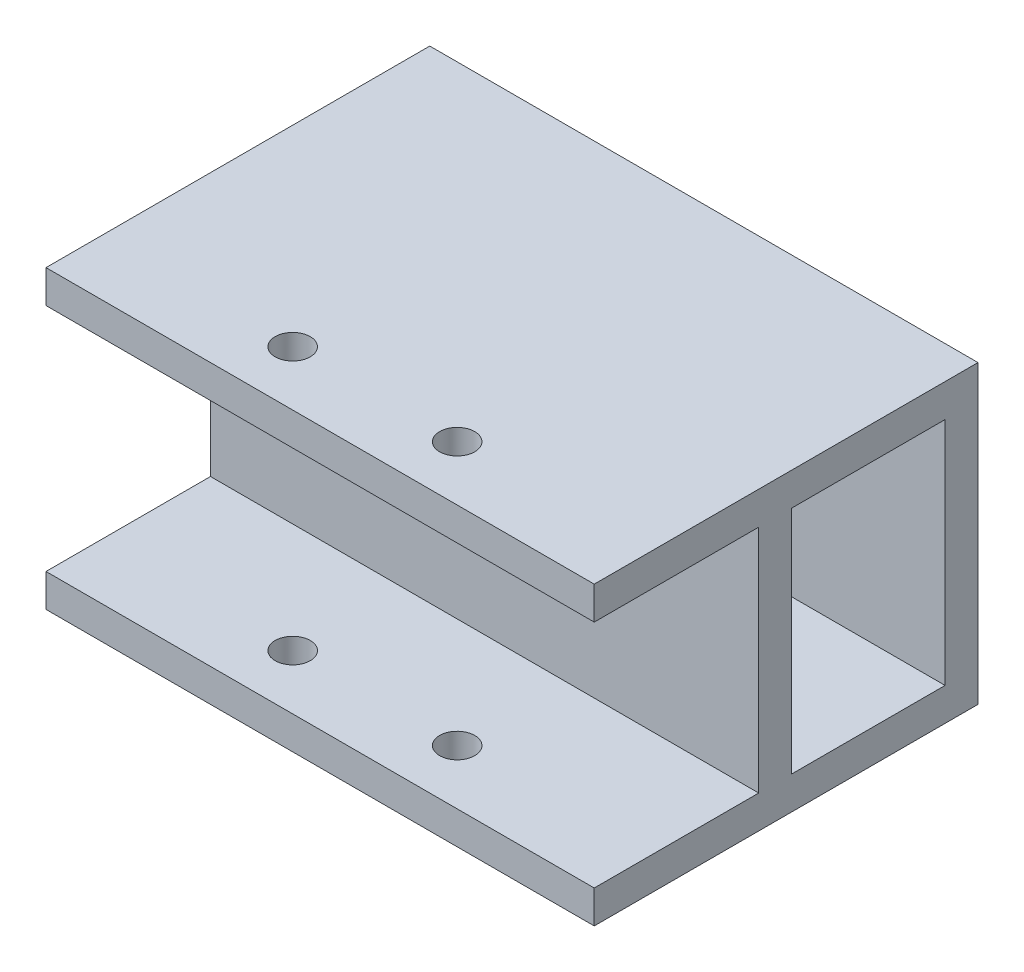
SolidWorks part; units mm, degrees
ref_plane "前视基准面" through (0, 0, 0) normal (0, 0, 1) x (1, 0, 0)
ref_plane "上视基准面" through (0, 0, 0) normal (0, 1, 0) x (1, 0, 0)
ref_plane "右视基准面" through (0, 0, 0) normal (1, 0, 0) x (0, 0, -1)
other "Configuration Table"
sketch "草图1" plane through (0, 0, 0) normal (0, 0, 1) x (1, 0, 0)
  line L1 (-21.1991, 13.3298) -> (28.8009, 13.3298)
  line L2 (-21.1991, 13.3298) -> (-21.1991, -13.6702)
  line L3 (-21.1991, -13.6702) -> (28.8009, -13.6702)
  line L4 (28.8009, 13.3298) -> (28.8009, -13.6702)
  dimension "D1" = 50
  dimension "D2" = 27
extrude "凸台-拉伸1" add sketch "草图1" along normal blind 35
sketch "草图2" plane through (0, 0, 35) normal (0, 0, 1) x (1, 0, 0)
  line L0 (-21.1991, 13.3298) -> (-21.1991, -13.6702) construction
  line L1 (-21.1991, 10.3298) -> (28.8009, 10.3298)
  line L2 (-21.1991, 10.3298) -> (-21.1991, -10.6702)
  line L3 (-21.1991, -10.6702) -> (28.8009, -10.6702)
  line L4 (28.8009, 10.3298) -> (28.8009, -10.6702)
  line L5 (28.8009, -13.6702) -> (28.8009, 13.3298) construction
  line L6 (28.8009, 13.3298) -> (-21.1991, 13.3298) construction
  line L7 (-21.1991, -13.6702) -> (28.8009, -13.6702) construction
  dimension "D1" = 3
  dimension "D2" = 3
extrude "切除-拉伸1" cut sketch "草图2" against normal blind 15
sketch "草图3" plane through (0, -13.6702, 0) normal (0, -1, 0) x (1, 0, 0)
  line L0 (28.8009, 35) -> (28.8009, 0) construction
  line L1 (-21.1991, 35) -> (28.8009, 35)
  line L2 (-21.1991, 35) -> (-21.1991, 25)
  line L3 (-21.1991, 25) -> (28.8009, 25)
  line L4 (28.8009, 35) -> (28.8009, 25)
  line L5 (-21.1991, 30) -> (28.8009, 30) construction
  line L6 (3.8009, 35) -> (3.8009, 25) construction
  circle A0 centre (-3.6991, 30) radius 1.6
  circle A1 centre (11.3009, 30) radius 1.6
  dimension "D4" = 3.2
  dimension "D1" = 10
  dimension "D2" = 7.5
  dimension "D3" = 7.5
extrude "切除-拉伸2" cut sketch "草图3" against normal through all contours A1 | A0
sketch "草图4" plane through (-21.1991, 0, 0) normal (-1, 0, 0) x (0, 0, 1)
  line L0 (35, 13.3298) -> (0, 13.3298) construction
  line L1 (3, 10.3298) -> (17, 10.3298)
  line L2 (3, 10.3298) -> (3, -10.6702)
  line L3 (3, -10.6702) -> (17, -10.6702)
  line L4 (17, 10.3298) -> (17, -10.6702)
  line L5 (35, -13.6702) -> (0, -13.6702) construction
  line L6 (20, 10.3298) -> (20, -10.6702) construction
  line L7 (0, 13.3298) -> (0, -13.6702) construction
  dimension "D1" = 3
  dimension "D2" = 3
  dimension "D3" = 3
  dimension "D4" = 3
extrude "切除-拉伸3" cut sketch "草图4" against normal through all
